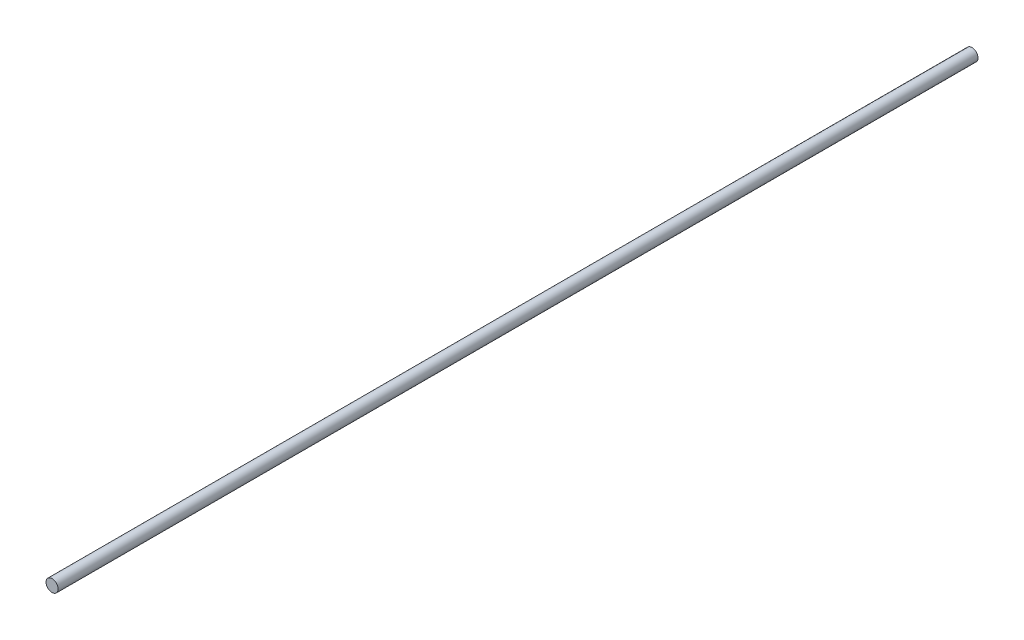
SolidWorks part; units mm, degrees
material "Thornel Mat VMA"
ref_plane "前视基准面" through (0, 0, 0) normal (0, 0, 1) x (1, 0, 0)
ref_plane "上视基准面" through (0, 0, 0) normal (0, 1, 0) x (1, 0, 0)
ref_plane "右视基准面" through (0, 0, 0) normal (1, 0, 0) x (0, 0, -1)
sketch "草图1" plane through (0, 0, 0) normal (0, 0, 1) x (1, 0, 0)
  circle A0 centre (0, 0) radius 0.75
  dimension "D1" = 1.5
extrude "凸台-拉伸1" add sketch "草图1" along normal blind 114
equation "\"m\"= 2"
